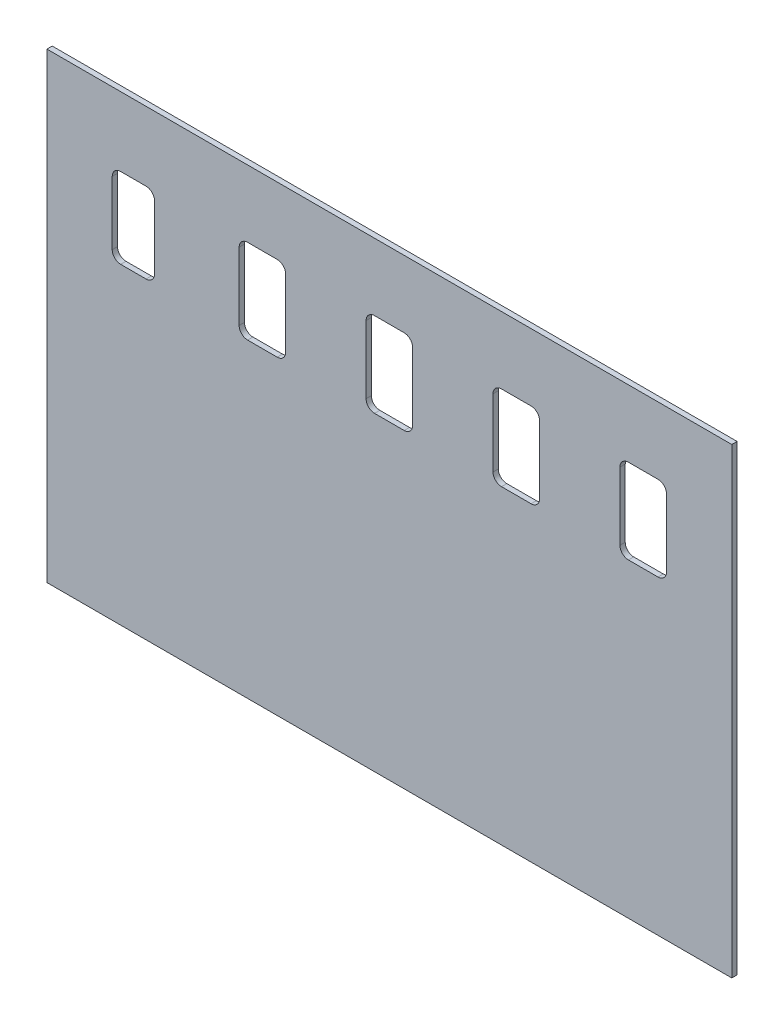
SolidWorks part; units mm, degrees
material "ABS PC"
ref_plane "Front Plane" through (0, 0, 0) normal (0, 0, 1) x (1, 0, 0)
ref_plane "Top Plane" through (0, 0, 0) normal (0, 1, 0) x (1, 0, 0)
ref_plane "Right Plane" through (0, 0, 0) normal (1, 0, 0) x (0, 0, -1)
sketch "Sketch1" plane through (0, 0, 0) normal (0, 0, 1) x (1, 0, 0)
  line L1 (-205.5812, -138.684) -> (205.5812, -138.684)
  line L2 (-205.5812, -138.684) -> (-205.5812, 138.684)
  line L3 (-205.5812, 138.684) -> (205.5812, 138.684)
  line L4 (205.5812, -138.684) -> (205.5812, 138.684)
  line L5 (0, 138.684) -> (0, -138.684) construction
  line L6 (-205.5812, 0) -> (205.5813, 0) construction
  point P0 (0, 0)
  point P4 (-137.0013, 0)
  point P5 (137.0013, 0)
  point P6 (0, 97.0788)
  point P7 (0, -97.0788)
  dimension "Width" = 277.368
  dimension "Break" = 68.58
  dimension "D2" = 68.58
  dimension "D1" = 41.6052
  dimension "D3" = 41.6052
  dimension "D4" = 411.1625
sketch "Sketch2" plane through (0, 0, 0) normal (1, 0, 0) x (0, 0, -1)
  line L0 (-1.5875, -138.684) -> (1.5875, -138.684)
  dimension "Thickness" = 3.175
sketch "Sketch3" plane through (0, 0, 0) normal (0, 0, 1) x (1, 0, 0)
  line L0 (-205.5812, -138.684) -> (-205.5812, 138.684) construction
  line L1 (-205.5812, -138.684) -> (205.5812, -138.684) construction
  line L2 (205.5812, -138.684) -> (205.5812, 138.684) construction
  line L3 (-205.5812, 138.684) -> (205.5812, 138.684) construction
  line L4 (-205.5812, -138.684) -> (-205.5812, 138.684)
  line L5 (-205.5812, -138.684) -> (205.5812, -138.684)
  line L6 (205.5812, -138.684) -> (205.5812, 138.684)
  line L7 (-205.5812, 138.684) -> (205.5812, 138.684)
extrude "Boss-Extrude1" add sketch "Sketch3" along normal mid plane 3.175
sketch "Sketch4" plane through (0, 0, 1.5875) normal (0, 0, 1) x (1, 0, 0)
  line L0 (-227.6475, 73.0327) -> (-161.29, 73.0327) construction
  line L1 (-82.55, 73.0327) -> (-82.55, 98.4327) construction
  line L2 (-82.55, 98.4327) -> (-90.17, 98.4327) construction
  line L3 (-161.29, 73.0327) -> (-161.29, 97.1627) construction
  line L6 (-227.6475, -105.791) -> (-227.6475, 52.959) construction
  line L7 (-227.6475, -115.316) -> (-227.6475, 138.684) construction
  line L8 (-161.29, 73.0327) -> (-82.55, 73.0327) construction
  line L9 (-82.55, 73.0327) -> (-6.35, 73.0327) construction
  line L10 (-6.35, 73.0327) -> (69.85, 73.0327) construction
  line L11 (69.85, 73.0327) -> (146.05, 73.0327) construction
  line L12 (-82.55, 73.0327) -> (-82.55, 47.6327) construction
  line L13 (-82.55, 47.6327) -> (-62.23, 47.6327) construction
  line L16 (-161.29, 97.1627) -> (-166.37, 97.1627) construction
  line L17 (-161.29, 73.0327) -> (-161.29, 48.9027) construction
  line L18 (-161.29, 48.9027) -> (-140.97, 48.9027) construction
  line L19 (-6.35, 73.0327) -> (-6.35, 98.4327) construction
  line L24 (-6.35, 98.4327) -> (-13.97, 98.4327) construction
  line L25 (-6.35, 73.0327) -> (-6.35, 47.6327) construction
  line L26 (-6.35, 47.6327) -> (13.97, 47.6327) construction
  line L27 (69.85, 73.0327) -> (69.85, 98.4327) construction
  line L28 (-8.89, 98.4327) -> (8.89, 98.4327)
  line L29 (-13.97, 93.3527) -> (-13.97, 52.7127)
  line L30 (-8.89, 47.6327) -> (8.89, 47.6327)
  line L31 (13.97, 93.3527) -> (13.97, 52.7127)
  line L32 (69.85, 98.4327) -> (62.23, 98.4327) construction
  line L33 (69.85, 73.0327) -> (69.85, 47.6327) construction
  line L34 (69.85, 47.6327) -> (90.17, 47.6327) construction
  line L35 (146.05, 73.0327) -> (146.05, 98.4327) construction
  line L36 (67.31, 98.4327) -> (85.09, 98.4327)
  line L37 (62.23, 93.3527) -> (62.23, 52.7127)
  line L38 (67.31, 47.6327) -> (85.09, 47.6327)
  line L39 (90.17, 93.3527) -> (90.17, 52.7127)
  line L40 (146.05, 98.4327) -> (138.43, 98.4327) construction
  line L41 (146.05, 73.0327) -> (146.05, 47.6327) construction
  line L42 (146.05, 47.6327) -> (166.37, 47.6327) construction
  line L43 (-205.5812, 138.684) -> (-205.5812, 73.0327) construction
  line L44 (143.51, 98.4327) -> (161.29, 98.4327)
  line L45 (138.43, 93.3527) -> (138.43, 52.7127)
  line L46 (143.51, 47.6327) -> (161.29, 47.6327)
  line L47 (166.37, 93.3527) -> (166.37, 52.7127)
  line L48 (-85.09, 98.4327) -> (-67.31, 98.4327)
  line L49 (-90.17, 93.3527) -> (-90.17, 52.7127)
  line L50 (-85.09, 47.6327) -> (-67.31, 47.6327)
  line L51 (-62.23, 93.3527) -> (-62.23, 52.7127)
  line L53 (-161.29, 97.1627) -> (-146.05, 97.1627)
  line L54 (-166.37, 92.0827) -> (-166.37, 53.9827)
  line L55 (-161.29, 48.9027) -> (-146.05, 48.9027)
  line L56 (-140.97, 92.0827) -> (-140.97, 53.9827)
  arc A0 (138.43, 52.7127) -> (143.51, 47.6327) centre (143.51, 52.7127) ccw
  arc A1 (166.37, 52.7127) -> (161.29, 47.6327) centre (161.29, 52.7127) cw
  arc A2 (161.29, 98.4327) -> (166.37, 93.3527) centre (161.29, 93.3527) cw
  arc A3 (138.43, 93.3527) -> (143.51, 98.4327) centre (143.51, 93.3527) cw
  arc A4 (62.23, 52.7127) -> (67.31, 47.6327) centre (67.31, 52.7127) ccw
  arc A5 (90.17, 52.7127) -> (85.09, 47.6327) centre (85.09, 52.7127) cw
  arc A6 (85.09, 98.4327) -> (90.17, 93.3527) centre (85.09, 93.3527) cw
  arc A7 (67.31, 98.4327) -> (62.23, 93.3527) centre (67.31, 93.3527) ccw
  arc A8 (-13.97, 52.7127) -> (-8.89, 47.6327) centre (-8.89, 52.7127) ccw
  arc A9 (13.97, 52.7127) -> (8.89, 47.6327) centre (8.89, 52.7127) cw
  arc A10 (8.89, 98.4327) -> (13.97, 93.3527) centre (8.89, 93.3527) cw
  arc A11 (-8.89, 98.4327) -> (-13.97, 93.3527) centre (-8.89, 93.3527) ccw
  arc A19 (-90.17, 52.7127) -> (-85.09, 47.6327) centre (-85.09, 52.7127) ccw
  arc A20 (-62.23, 52.7127) -> (-67.31, 47.6327) centre (-67.31, 52.7127) cw
  arc A21 (-67.31, 98.4327) -> (-62.23, 93.3527) centre (-67.31, 93.3527) cw
  arc A22 (-85.09, 98.4327) -> (-90.17, 93.3527) centre (-85.09, 93.3527) ccw
  arc A23 (-166.37, 53.9827) -> (-161.29, 48.9027) centre (-161.29, 53.9827) ccw
  arc A24 (-146.05, 48.9027) -> (-140.97, 53.9827) centre (-146.05, 53.9827) ccw
  arc A25 (-146.05, 97.1627) -> (-140.97, 92.0827) centre (-146.05, 92.0827) cw
  arc A26 (-161.29, 97.1627) -> (-166.37, 92.0827) centre (-161.29, 92.0827) ccw
  point P16 (-76.2, 98.4327)
  point P17 (-90.17, 73.0327)
  point P18 (-13.97, 73.0327)
  point P95 (62.23, 73.0327)
  point P96 (138.43, 73.0327)
  point P97 (0, 98.4327)
  point P98 (76.2, 98.4327)
  point P99 (152.4, 98.4327)
  dimension "D1" = 5.08
  dimension "D2" = 5.08
  dimension "D5" = 5.08
  dimension "D9" = 27.94
  dimension "D10" = 27.94
  dimension "D11" = 27.94
  dimension "D12" = 27.94
  dimension "D3" = 76.2
  dimension "D4" = 76.2
  dimension "D6" = 152.4
  dimension "D7" = 65.6513
extrude "Cut-Extrude1" cut sketch "Sketch4" against normal blind 25.4 contours L53 A26 L54 A23 L55 A24 L56 A25
equation "\"D1@Boss-Extrude1\" = \"Thickness@Sketch2\""
equation "\"D2@Sketch1\" = \"Break@Sketch1\""
equation "\"D1@Sketch1\"=\"Width@Sketch1\"*0.15"
equation "\"D3@Sketch1\"=\"D1@Sketch1\""
equation "\"SlotWidth\"= 1.1in"
equation "\"D9@Sketch4\"=\"SlotWidth\""
equation "\"D10@Sketch4\"=\"SlotWidth\""
equation "\"D11@Sketch4\"=\"SlotWidth\""
equation "\"D12@Sketch4\"=\"SlotWidth\""
